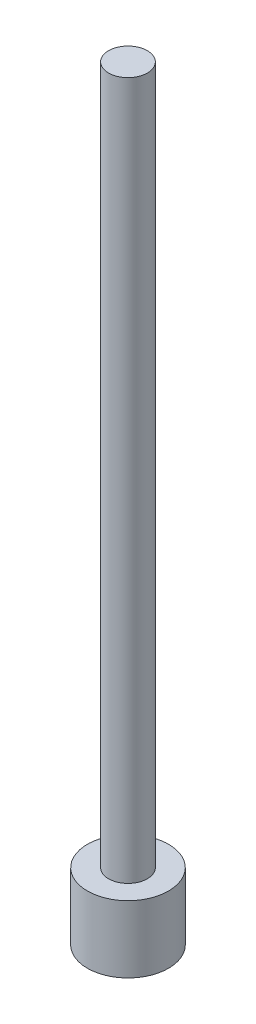
SolidWorks part; units mm, degrees
ref_plane "Front Plane" through (0, 0, 0) normal (0, 0, 1) x (1, 0, 0)
ref_plane "Top Plane" through (0, 0, 0) normal (0, 1, 0) x (1, 0, 0)
ref_plane "Right Plane" through (0, 0, 0) normal (1, 0, 0) x (0, 0, -1)
sketch "Sketch2" plane through (0, 0, 0) normal (0, 1, 0) x (1, 0, 0)
  circle A0 centre (0, 0) radius 2.875
  dimension "D1" = 5.75
extrude "Boss-Extrude1" add sketch "Sketch2" along normal blind 4.75
sketch "Sketch3" plane through (0, 4.75, 0) normal (0, 1, 0) x (1, 0, 0)
  circle A0 centre (0, 0) radius 1.375
  dimension "D1" = 2.75
extrude "Boss-Extrude2" add sketch "Sketch3" along normal blind 49.5
